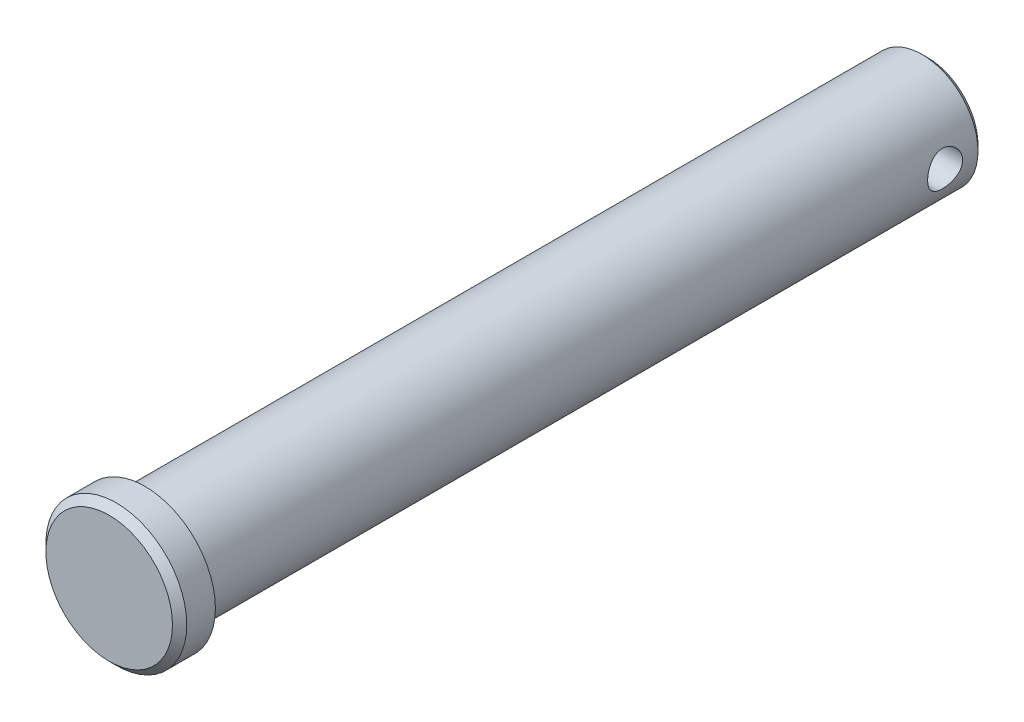
SolidWorks part; units mm, degrees
material "AISI 304"
ref_plane "Front" through (0, 0, 0) normal (0, 0, 1) x (1, 0, 0)
ref_plane "Top" through (0, 0, 0) normal (0, 1, 0) x (1, 0, 0)
ref_plane "Right" through (0, 0, 0) normal (1, 0, 0) x (0, 0, -1)
sketch "Sketch1" plane through (0, 0, 0) normal (0, 0, 1) x (1, 0, 0)
  circle A0 centre (0, 0) radius 6.35
  point P3 (0, 6.35)
  point P4 (0, -6.35)
  dimension "dia" = 12.7
extrude "Extrude1" add sketch "Sketch1" along normal mid plane 88.9
sketch "Sketch2" plane through (0, 0, 44.45) normal (0, 0, 1) x (1, 0, 0)
  circle A0 centre (0, 0) radius 8.001
  dimension "head dia" = 16.002
extrude "Extrude2" add sketch "Sketch2" along normal blind 4.064
chamfer "Chamfer1" distance 0.8128 angle 45 1 edges at (8.001, 0, 48.514)
sketch "Sketch3" plane through (0, 0, 0) normal (1, 0, 0) x (0, 0, -1)
  line L0 (-44.45, -6.35) -> (-44.45, 6.35) construction
  circle A0 centre (40.0844, 0) radius 1.9844
  point P2 (38.1, 0)
  dimension "hole dia" = 3.9688
  dimension "useable Lg" = 82.55
extrude "Extrude3" cut sketch "Sketch3" against normal through all and the other way through all
chamfer "Chamfer2" distance 0.635 angle 45 1 edges at (6.35, 0, -44.45)
ref_plane "Plane1" through (0, 0, -40.0844) normal (0, 0, 1) x (1, 0, 0)
sketch "Sketch8" plane through (0, 0, 0) normal (1, 0, 0) x (0, 0, -1)
  line L0 (-48.514, 7.1882) -> (-48.514, -7.1882) construction
  line L1 (-47.7012, -8.001) -> (-44.45, -8.001) construction
  line L2 (44.45, -5.715) -> (44.45, 5.715) construction
  point P0 (-48.514, 8.001)
  point P1 (-44.45, 8.001)
  point P5 (44.45, 6.35)
  point P8 (-48.514, -8.001)
  point P9 (44.45, -6.35)
equation "\"D1@Chamfer1\" = \"head ht@Extrude2\" * .2"
equation "\"D1@Chamfer2\" = \"dia@Sketch1\" * .05"
